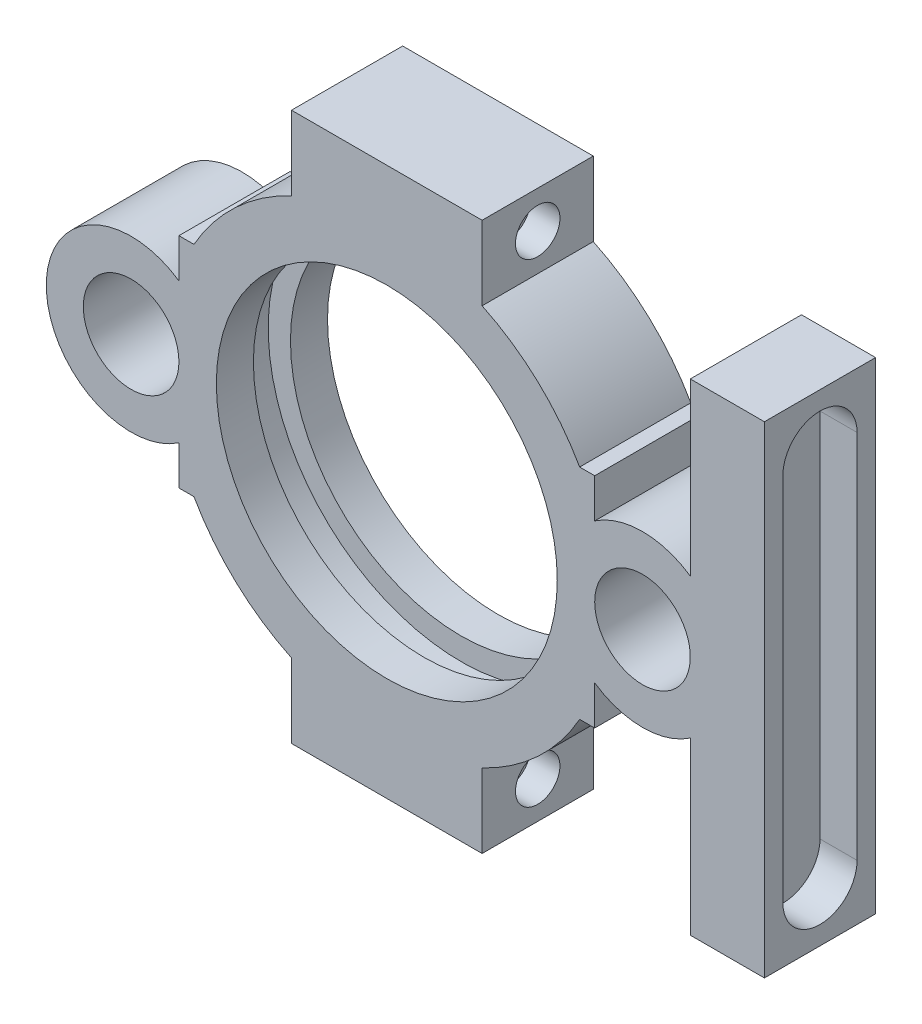
SolidWorks part; units mm, degrees
ref_plane "Front Plane" through (0, 0, 0) normal (0, 0, 1) x (1, 0, 0)
ref_plane "Top Plane" through (0, 0, 0) normal (0, 1, 0) x (1, 0, 0)
ref_plane "Right Plane" through (0, 0, 0) normal (1, 0, 0) x (0, 0, -1)
sketch "Sketch1" plane through (0, 0, 0) normal (0, 0, 1) x (1, 0, 0)
  line L0 (0, 23) -> (0, 37)
  line L1 (0, 37) -> (12.8595, 37)
  line L2 (12.8595, 37) -> (12.8595, 27)
  line L3 (0, 0) -> (90, 0) construction
  line L4 (26.0205, 14.7412) -> (28.0505, 14.7412)
  line L5 (28.0505, 25) -> (28.0505, -25) construction
  line L6 (28.0505, 14.7412) -> (28.0505, 9.4604)
  line L7 (40.9505, 9.4604) -> (40.9505, 32.5)
  line L8 (40.9505, 32.5) -> (50.9505, 32.5)
  line L9 (50.9505, 32.5) -> (50.9505, -32.5)
  line L10 (40.9505, -32.5) -> (50.9505, -32.5)
  line L11 (40.9505, -9.4604) -> (40.9505, -32.5)
  line L12 (28.0505, -14.7412) -> (28.0505, -9.4604)
  line L13 (26.0205, -14.7412) -> (28.0505, -14.7412)
  line L14 (12.8595, -37) -> (12.8595, -27)
  line L15 (0, -37) -> (12.8595, -37)
  line L16 (0, -23) -> (0, -37)
  arc A0 (0, 23) -> (0, -23) centre (0, 0) cw
  arc A1 (12.8595, 27) -> (26.0205, 14.7412) centre (0, 0) cw
  circle A2 centre (34.5005, 0) radius 6.45
  arc A3 (28.0505, 9.4604) -> (40.9505, 9.4604) centre (34.5005, 0) cw
  arc A4 (28.0505, -9.4604) -> (40.9505, -9.4604) centre (34.5005, 0) ccw
  arc A5 (12.8595, -27) -> (26.0205, -14.7412) centre (0, 0) ccw
  point P8 (28.0505, 0)
  point P19 (50.9505, 0)
  point P29 (40.9505, 0)
  dimension "D2" = 23
  dimension "D5" = 35
  dimension "D7" = 6.45
  dimension "D8" = 50
  dimension "D9" = 29.906
  dimension "D10" = 11.45
  dimension "D3" = 14
  dimension "D4" = 10
  dimension "D6" = 2.03
  dimension "D11" = 90
  dimension "D12" = 10
  dimension "D13" = 32.5
extrude "Boss-Extrude1" add sketch "Sketch1" along normal blind 15
ref_plane "Plane1" through (0, 0, 0) normal (-1, 0, 0) x (0, 0, 1)
sketch "Sketch2" plane through (0, 0, 0) normal (-1, 0, 0) x (0, 0, 1)
  line L0 (7.5, 37) -> (7.5, 23) construction
  line L1 (15, 37) -> (0, 37) construction
  line L2 (15, 23) -> (0, 23) construction
  line L3 (10, 26) -> (5, 26)
  line L4 (5, 26) -> (5, 23)
  line L5 (10, 26) -> (10, 23)
  line L6 (5, 23) -> (10, 23)
  line L7 (15, 0) -> (0, 0) construction
  line L8 (15, -23) -> (15, 23) construction
  point P10 (7.5, 26)
  dimension "D1" = 2.5
  dimension "D2" = 3
revolve "Cut-Revolve1" cut sketch "Sketch2" angle 360 about L7
ref_plane "Plane2" through (50.9505, 0, 0) normal (1, 0, 0) x (0, 0, -1)
sketch "Sketch3" plane through (50.9505, 0, 0) normal (1, 0, 0) x (0, 0, -1)
  line L0 (-15, 0) -> (0, 0) construction
  line L1 (-15, -32.5) -> (-15, 32.5) construction
  line L2 (-7.5, 32.5) -> (-7.5, -32.5) construction
  line L3 (-15, 32.5) -> (0, 32.5) construction
  line L5 (-15, -32.5) -> (0, -32.5) construction
  line L8 (-12.5, -25) -> (-12.5, 25)
  line L10 (-2.5, -25) -> (-2.5, 25)
  line L11 (-12.5, -25) -> (-2.5, 25) construction
  line L12 (-12.5, 25) -> (-2.5, -25) construction
  arc A0 (-12.5, 25) -> (-2.5, 25) centre (-7.5, 25) cw
  arc A1 (-12.5, -25) -> (-2.5, -25) centre (-7.5, -25) ccw
  point P14 (-7.5, 0)
  dimension "D1" = 50
  dimension "D2" = 10
extrude "Cut-Extrude3" cut sketch "Sketch3" against normal blind 5
ref_plane "Plane3" through (12.8595, 0, 0) normal (1, 0, 0) x (0, 0, -1)
sketch "Sketch4" plane through (12.8595, 0, 0) normal (1, 0, 0) x (0, 0, -1)
  line L0 (-7.5, 37) -> (-7.5, 27) construction
  line L1 (-15, 37) -> (0, 37) construction
  line L2 (-15, 27) -> (0, 27) construction
  line L3 (-15, 32) -> (0, 32) construction
  line L4 (-15, 27) -> (-15, 37) construction
  line L5 (0, 27) -> (0, 37) construction
  line L6 (-15, 0) -> (1.8408, 0) construction
  circle A0 centre (-7.3334, 32) radius 1.5
  circle A1 centre (-7.3334, -32) radius 1.5
  dimension "D1" = 3
extrude "Cut-Extrude4" cut sketch "Sketch4" along normal blind 23 and the other way blind 40 contours A0 | A1
sketch "Sketch5" plane through (12.8595, 0, 0) normal (1, 0, 0) x (0, 0, -1)
  line L0 (-7.5, 37) -> (-7.5, 27) construction
  line L1 (-15, 37) -> (0, 37) construction
  line L2 (-15, 27) -> (0, 27) construction
  line L3 (-15, 32) -> (0, 32) construction
  line L4 (-15, 27) -> (-15, 37) construction
  line L5 (0, 27) -> (0, 37) construction
  line L6 (-15, 0) -> (6.1086, 0) construction
  circle A0 centre (-7.5, 32) radius 3
  circle A1 centre (-7.5, -32) radius 3
  dimension "D1" = 6
extrude "Cut-Extrude5" cut sketch "Sketch5" against normal blind 4
mirror "Mirror1" about plane through (0, 0, 0) normal (-1, 0, 0) of "Cut-Extrude4", "Cut-Extrude5", "Cut-Revolve1", "Boss-Extrude1"
sketch "Sketch6" plane through (0, 0, 15) normal (0, 0, 1) x (1, 0, 0)
  line L0 (-40.9505, 9.4604) -> (-40.9505, 38.7418)
  line L1 (-40.9505, 38.7418) -> (-62.7725, 38.7418)
  line L2 (-62.7725, 38.7418) -> (-62.7725, -39.4714)
  line L3 (-62.7725, -39.4714) -> (-40.9505, -39.4714)
  line L4 (-40.9505, -39.4714) -> (-40.9505, -9.4604)
  arc A0 (-40.9505, 9.4604) -> (-40.9505, -9.4604) centre (-34.5005, 0) ccw
  dimension "D1" = 22.9
extrude "Cut-Extrude6" cut sketch "Sketch6" against normal blind 80
